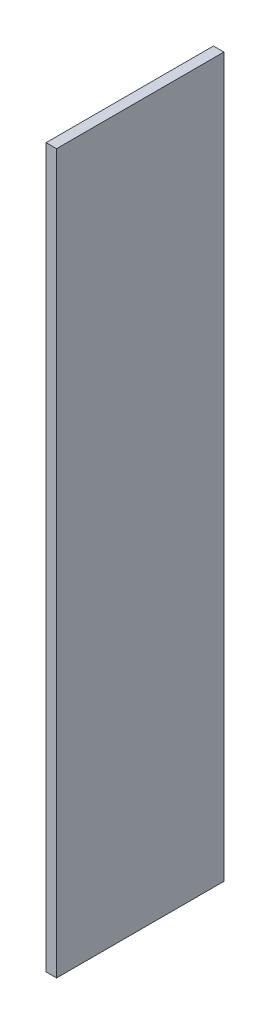
SolidWorks part; units mm, degrees
ref_plane "Front Plane" through (0, 0, 0) normal (0, 0, 1) x (1, 0, 0)
ref_plane "Top Plane" through (0, 0, 0) normal (0, 1, 0) x (1, 0, 0)
ref_plane "Right Plane" through (0, 0, 0) normal (1, 0, 0) x (0, 0, -1)
sketch "Sketch1" plane through (0, 0, 0) normal (1, 0, 0) x (0, 0, -1)
  line L1 (-24, -103) -> (24, -103)
  line L2 (-24, -103) -> (-24, 103)
  line L3 (-24, 103) -> (24, 103)
  line L4 (24, -103) -> (24, 103)
  line L5 (-24, -103) -> (24, 103) construction
  line L6 (-24, 103) -> (24, -103) construction
  point P0 (0, 0)
  dimension "D1" = 206
  dimension "D2" = 48
extrude "Boss-Extrude1" add sketch "Sketch1" along normal blind 3
